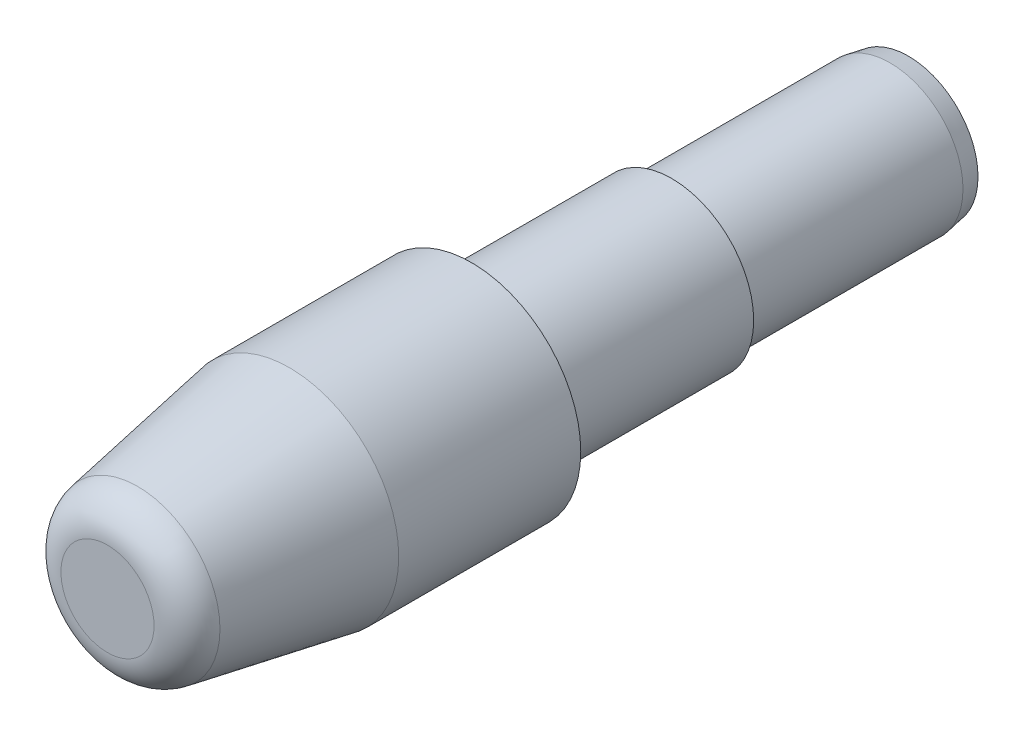
SolidWorks part; units mm, degrees
ref_plane "Alzado" through (0, 0, 0) normal (0, 0, 1) x (1, 0, 0)
ref_plane "Planta" through (0, 0, 0) normal (0, 1, 0) x (1, 0, 0)
ref_plane "Vista lateral" through (0, 0, 0) normal (1, 0, 0) x (0, 0, -1)
sketch "Croquis1" plane through (0, 0, 0) normal (0, 0, 1) x (1, 0, 0)
  circle A0 centre (0, 0) radius 6
  dimension "D1" = 12
extrude "Saliente-Extruir1" add sketch "Croquis1" along normal blind 10
sketch "Croquis2" plane through (0, 0, 10) normal (0, 0, 1) x (1, 0, 0)
  circle A0 centre (0, 0) radius 6
extrude "Saliente-Extruir2" add sketch "Croquis2" along normal blind 10
chamfer "Chaflán1" distance 10 angle 10 1 edges at (6, 0, 20)
fillet "Redondeo1" radius 2 1 edges at (4.2367, 0, 20)
sketch "Croquis3" plane through (0, 0, 0) normal (0, 0, -1) x (-1, 0, 0)
  circle A0 centre (0, 0) radius 4.5
  dimension "D1" = 9
extrude "Saliente-Extruir3" add sketch "Croquis3" along normal blind 11
sketch "Croquis4" plane through (0, 0, -11) normal (0, 0, -1) x (-1, 0, 0)
  circle A0 centre (0, 0) radius 4
  dimension "D1" = 8
extrude "Saliente-Extruir4" add sketch "Croquis4" along normal blind 13
chamfer "Chaflán2" distance 1 angle 10 1 edges at (-4, 0, -24)
